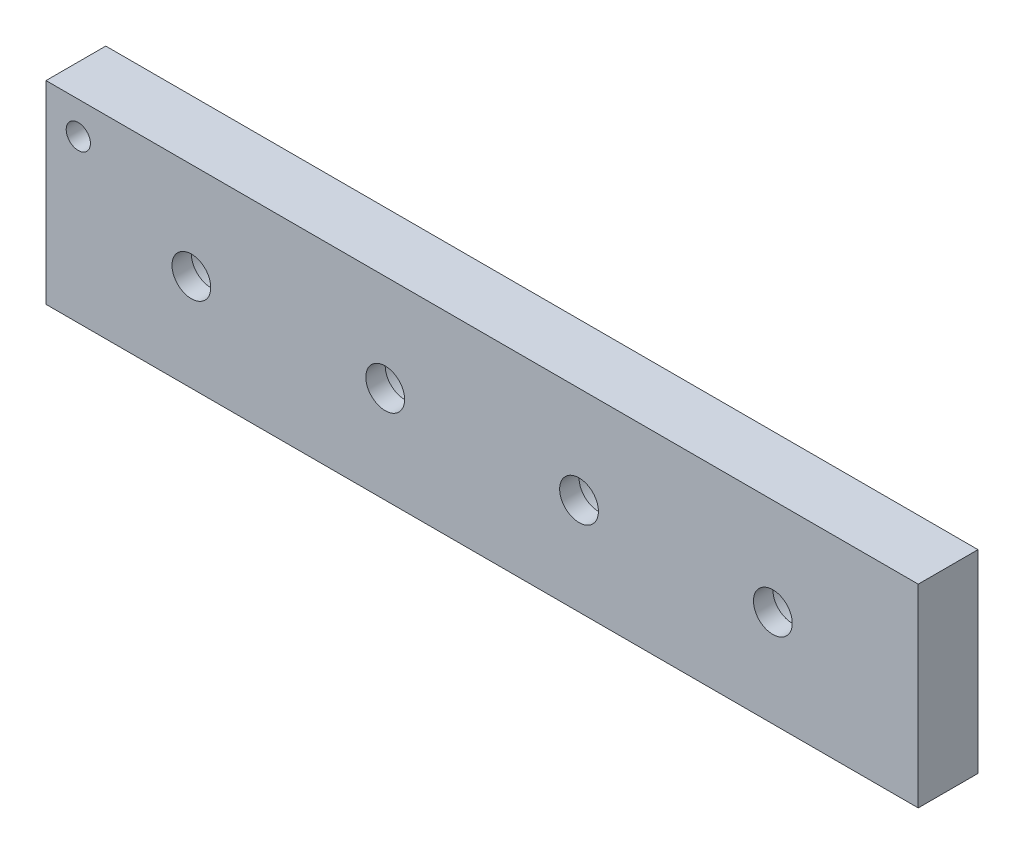
SolidWorks part; units mm, degrees
ref_plane "Front Plane" through (0, 0, 0) normal (0, 0, 1) x (1, 0, 0)
ref_plane "Top Plane" through (0, 0, 0) normal (0, 1, 0) x (1, 0, 0)
ref_plane "Right Plane" through (0, 0, 0) normal (1, 0, 0) x (0, 0, -1)
sketch "Coupon_bar_54x12x3p7_profile" plane through (0, 0, 0) normal (0, 0, 1) x (1, 0, 0)
  line L1 (-27, -6) -> (27, -6)
  line L2 (-27, -6) -> (-27, 6)
  line L3 (-27, 6) -> (27, 6)
  line L4 (27, -6) -> (27, 6)
  dimension "D1" = 54
  dimension "D2" = 12
extrude "Coupon_bar_54x12x3p7" add sketch "Coupon_bar_54x12x3p7_profile" along normal blind 3.7
sketch "Press_sockets_4p65_4p75_4p85_4p95_depth2p5_profile" plane through (0, 0, 0) normal (0, 0, 1) x (1, 0, 0)
  circle A0 centre (-18, 0) radius 2.325
  circle A1 centre (-6, 0) radius 2.375
  circle A2 centre (6, 0) radius 2.425
  circle A3 centre (18, 0) radius 2.475
  dimension "D1" = 4.65
  dimension "D2" = 4.75
  dimension "D3" = 4.85
  dimension "D4" = 4.95
extrude "Press_sockets_4p65_4p75_4p85_4p95_depth2p5" cut sketch "Press_sockets_4p65_4p75_4p85_4p95_depth2p5_profile" along normal blind 2.5
sketch "M2_centre_screw_clearance_profile" plane through (0, 0, 0) normal (0, 0, 1) x (1, 0, 0)
  circle A0 centre (-18, 0) radius 1.2
  circle A1 centre (-6, 0) radius 1.2
  circle A2 centre (6, 0) radius 1.2
  circle A3 centre (18, 0) radius 1.2
  dimension "D1" = 2.4
  dimension "D2" = 2.4
  dimension "D3" = 2.4
  dimension "D4" = 2.4
extrude "M2_centre_screw_clearance" cut sketch "M2_centre_screw_clearance_profile" along normal through all from offset 50
sketch "Orientation_mark_at_smallest_socket_profile" plane through (0, 0, 0) normal (0, 0, 1) x (1, 0, 0)
  circle A0 centre (-25, 4) radius 0.75
  dimension "D1" = 1.5
extrude "Orientation_mark_at_smallest_socket" cut sketch "Orientation_mark_at_smallest_socket_profile" along normal through all from offset 50
